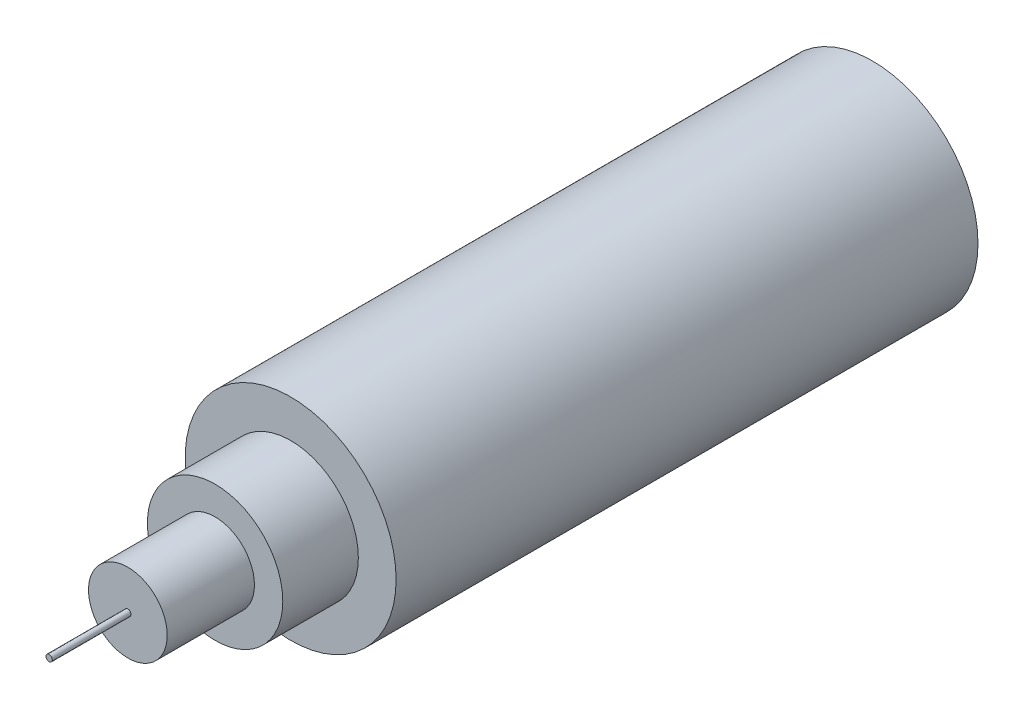
SolidWorks part; units mm, degrees
ref_plane "Front Plane" through (0, 0, 0) normal (0, 0, 1) x (1, 0, 0)
ref_plane "Top Plane" through (0, 0, 0) normal (0, 1, 0) x (1, 0, 0)
ref_plane "Right Plane" through (0, 0, 0) normal (1, 0, 0) x (0, 0, -1)
sketch "Sketch1" plane through (0, 0, 0) normal (0, 0, 1) x (1, 0, 0)
  circle A0 centre (0, 0) radius 33.5
  dimension "D1" = 67
extrude "Boss-Extrude1" add sketch "Sketch1" along normal blind 184.8
sketch "Sketch2" plane through (0, 0, 184.8) normal (0, 0, 1) x (1, 0, 0)
  circle A0 centre (0, 0) radius 21.5
  dimension "D1" = 43
extrude "Boss-Extrude2" add sketch "Sketch2" along normal blind 24
sketch "Sketch3" plane through (0, 0, 208.8) normal (0, 0, 1) x (1, 0, 0)
  circle A0 centre (0, 0) radius 12.5
  dimension "D1" = 25
extrude "Boss-Extrude3" add sketch "Sketch3" along normal blind 27.7
sketch "Sketch4" plane through (0, 0, 236.5) normal (0, 0, 1) x (1, 0, 0)
  circle A0 centre (0, 0) radius 1
  dimension "D1" = 2
extrude "Boss-Extrude4" add sketch "Sketch4" along normal blind 25
